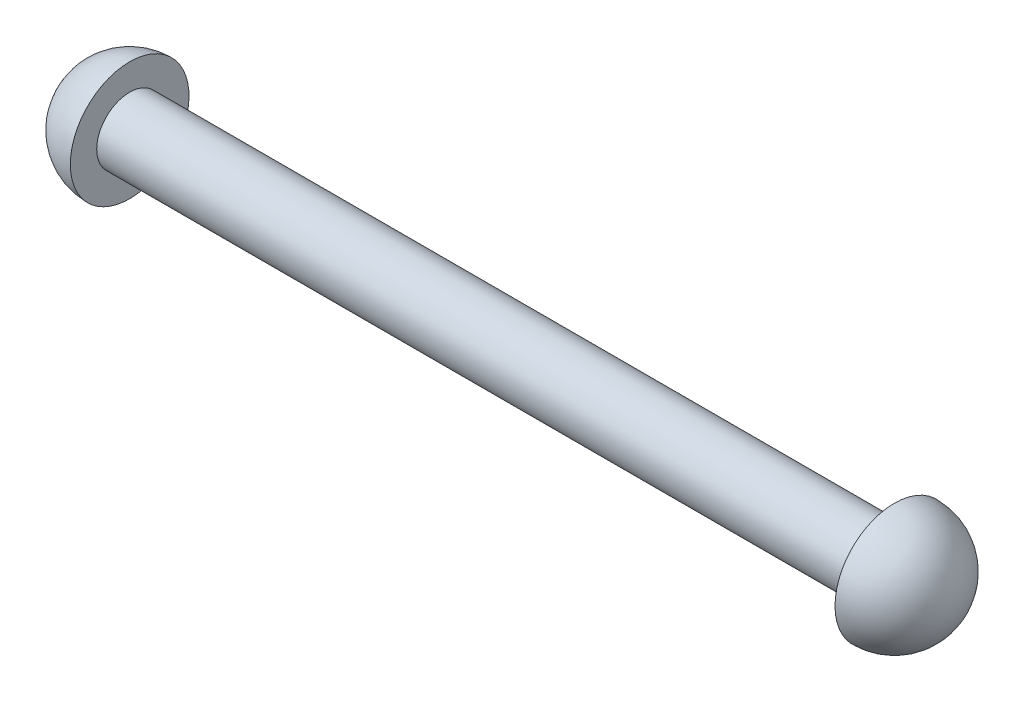
SolidWorks part; units mm, degrees
ref_plane "Front Plane" through (0, 0, 0) normal (0, 0, 1) x (1, 0, 0)
ref_plane "Top Plane" through (0, 0, 0) normal (0, 1, 0) x (1, 0, 0)
ref_plane "Right Plane" through (0, 0, 0) normal (1, 0, 0) x (0, 0, -1)
sketch "Sketch1" plane through (0, 0, 0) normal (0, 0, 1) x (1, 0, 0)
  line L0 (0, 0) -> (0, 5.715) construction
  line L2 (-36.83, 0) -> (-36.83, 3.175)
  line L3 (-36.83, 3.175) -> (36.83, 3.175)
  line L4 (36.83, 0) -> (36.83, 3.175)
  line L5 (0, 0) -> (36.83, 3.175) construction
  line L6 (-36.83, 3.175) -> (0, 0) construction
  line L7 (-36.83, 3.175) -> (-36.83, 5.715)
  line L10 (36.83, 3.175) -> (36.83, 5.715)
  line L11 (-42.545, 0) -> (42.545, 0)
  arc A0 (-36.83, 5.715) -> (-42.545, 0) centre (-36.83, 0) ccw
  arc A1 (36.83, 5.715) -> (42.545, 0) centre (36.83, 0) cw
  point P0 (0, 0)
  dimension "D3" = 11.43
  dimension "D1" = 3.175
  dimension "D2" = 73.66
revolve "Revolve3" add sketch "Sketch1" angle 360 about L11
